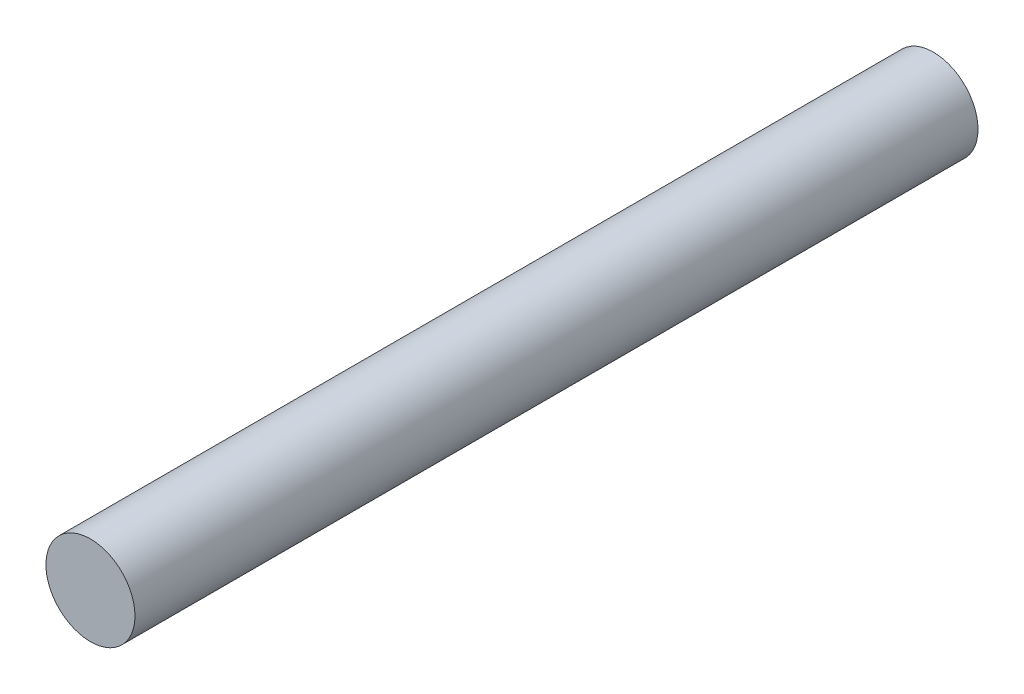
SolidWorks part; units mm, degrees
ref_plane "Спереди" through (0, 0, 0) normal (0, 0, 1) x (1, 0, 0)
ref_plane "Сверху" through (0, 0, 0) normal (0, 1, 0) x (1, 0, 0)
ref_plane "Справа" through (0, 0, 0) normal (1, 0, 0) x (0, 0, -1)
sketch "Эскиз1" plane through (0, 0, 0) normal (0, 0, 1) x (1, 0, 0)
  circle A0 centre (0, 0) radius 9
extrude "Вытянуть1" add sketch "Эскиз1" along normal blind 170.35
